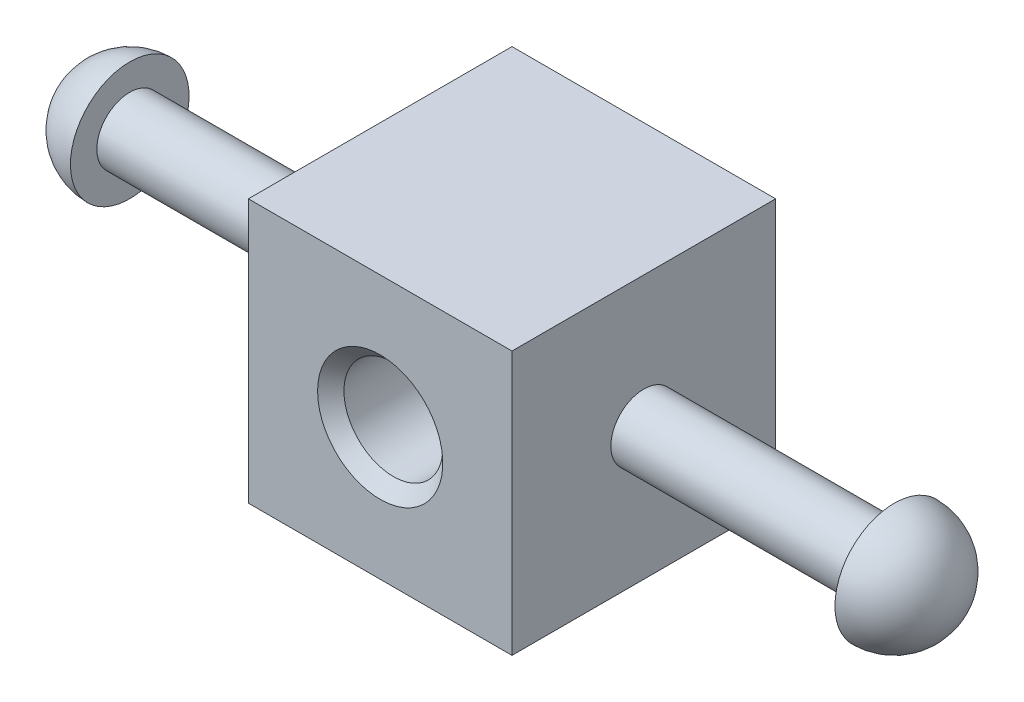
SolidWorks part; units mm, degrees
material "AISI 1020"
ref_plane "Front Plane" through (0, 0, 0) normal (0, 0, 1) x (1, 0, 0)
ref_plane "Top Plane" through (0, 0, 0) normal (0, 1, 0) x (1, 0, 0)
ref_plane "Right Plane" through (0, 0, 0) normal (1, 0, 0) x (0, 0, -1)
sketch "Sketch1" plane through (0, 0, 0) normal (0, 0, 1) x (1, 0, 0)
  line L1 (25.4, 25.4) -> (0, 25.4)
  line L2 (25.4, 25.4) -> (25.4, 0)
  line L3 (25.4, 0) -> (0, 0)
  line L4 (0, 25.4) -> (0, 0)
  circle A0 centre (12.7, 12.7) radius 4.7625
  point P5 (12.7, 0)
  point P8 (0, 12.7)
  dimension "D3" = 9.525
  dimension "D1" = 25.4
  dimension "D2" = 25.4
extrude "Boss-Extrude1" add sketch "Sketch1" along normal blind 25.4
chamfer "Chamfer1" distance 1.27 angle 45 2 edges at (17.4625, 12.7, 0) (17.4625, 12.7, 25.4)
ref_plane "Plane1" through (0, 0, 12.7) normal (0, 0, 1) x (1, 0, 0)
sketch "Sketch3" plane through (0, 0, 12.7) normal (0, 0, 1) x (1, 0, 0)
  line L0 (12.7, 25.4) -> (12.7, 0) construction
  line L1 (25.4, 25.4) -> (0, 25.4) construction
  line L2 (0, 0) -> (25.4, 0) construction
  line L3 (0, 25.4) -> (0, 0) construction
  line L6 (0, 12.7) -> (-24.13, 12.7)
  line L7 (0, 12.7) -> (0, 15.875)
  line L8 (0, 15.875) -> (-24.13, 15.875)
  line L9 (-24.13, 12.7) -> (-24.13, 15.875)
  line L10 (-29.845, 12.7) -> (-24.13, 12.7)
  line L12 (-24.13, 18.415) -> (-24.13, 12.7)
  arc A0 (-24.13, 18.415) -> (-29.845, 12.7) centre (-24.13, 12.7) ccw
  point P15 (12.7, 12.7)
  dimension "D3" = 5.715
  dimension "D1" = 3.175
  dimension "D2" = 36.83
revolve "Revolve5" add sketch "Sketch3" angle 360 about L6
sketch "Sketch4" plane through (0, 0, 12.7) normal (0, 0, 1) x (1, 0, 0)
  line L0 (25.4, 0) -> (25.4, 25.4) construction
  line L1 (25.4, 12.7) -> (49.53, 12.7)
  line L2 (25.4, 12.7) -> (25.4, 15.875)
  line L3 (25.4, 15.875) -> (49.53, 15.875)
  line L4 (49.53, 12.7) -> (49.53, 15.875)
  line L5 (-24.13, 6.985) -> (-24.13, 18.415) construction
  line L6 (49.53, 18.415) -> (49.53, 12.7)
  line L7 (55.245, 12.7) -> (49.53, 12.7)
  arc A0 (55.245, 12.7) -> (49.53, 18.415) centre (49.53, 12.7) ccw
  dimension "D3" = 5.715
  dimension "D1" = 73.66
  dimension "D2" = 3.175
revolve "Revolve6" add sketch "Sketch4" angle 360 about L1
